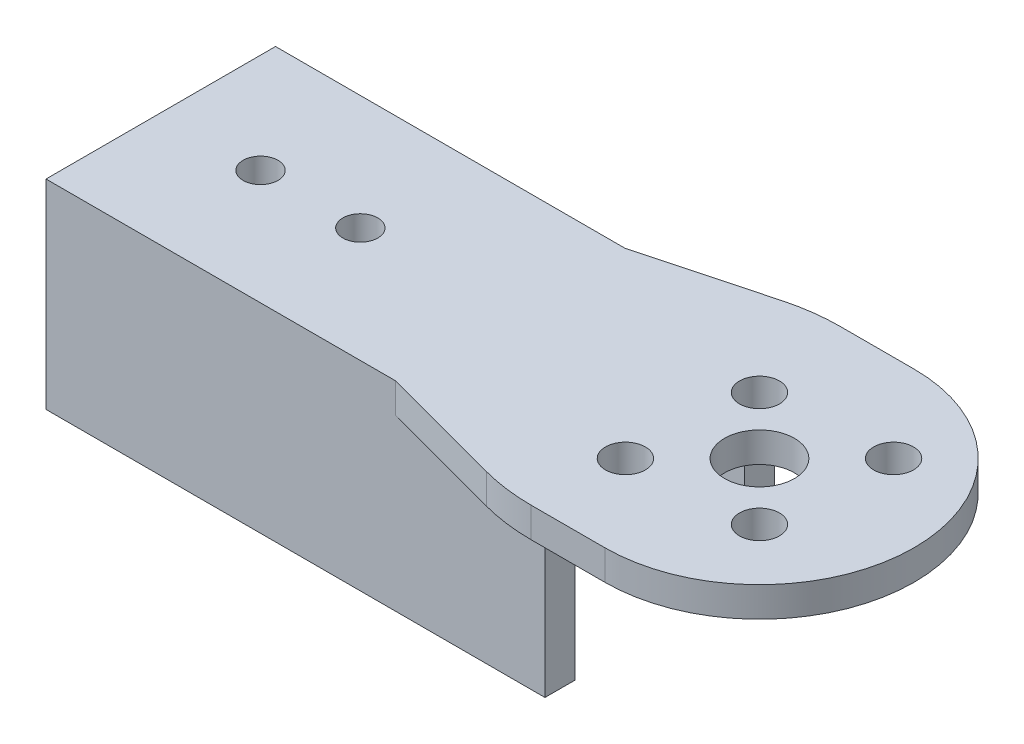
SolidWorks part; units mm, degrees
other "Markup1"
sketch "Sketch5" plane through (-25, 20, -29) normal (0, 1, 0) x (1, 0, 0)
sketch "Sketch6" plane through (-25, 20, -15) normal (0, 1, 0) x (1, 0, 0)
sketch "Sketch7" plane through (-25, 20, -15) normal (0, 1, 0) x (1, 0, 0)
sketch "Sketch8" plane through (-25, 20, -15.5) normal (0, 1, 0) x (1, 0, 0)
ref_plane "Front Plane" through (0, 0, 0) normal (0, 0, 1) x (1, 0, 0)
ref_plane "Top Plane" through (0, 0, 0) normal (0, 1, 0) x (1, 0, 0)
ref_plane "Right Plane" through (0, 0, 0) normal (1, 0, 0) x (0, 0, -1)
sketch "Sketch1" plane through (0, 0, 0) normal (0, 1, 0) x (1, 0, 0)
  line L1 (-25, 11.5) -> (25, 11.5)
  line L2 (-25, 11.5) -> (-25, -11.5)
  line L3 (-25, -11.5) -> (25, -11.5)
  line L4 (25, 11.5) -> (25, -11.5)
  line L5 (-25, 11.5) -> (25, -11.5) construction
  line L6 (-25, -11.5) -> (25, 11.5) construction
  point P0 (0, 0)
  dimension "D1" = 23
  dimension "D2" = 50
extrude "Boss-Extrude1" add sketch "Sketch1" along normal blind 20
sketch "Sketch2" plane through (25, 0, 0) normal (1, 0, 0) x (0, 0, -1)
  line L0 (55, 0) -> (-55, 0) construction
  line L1 (-8.5, 0) -> (8.5, 0)
  line L2 (-8.5, 0) -> (-8.5, 17)
  line L3 (-8.5, 17) -> (8.5, 17)
  line L4 (8.5, 0) -> (8.5, 17)
  line L5 (11.5, 20) -> (11.5, 0) construction
  line L6 (-11.5, 20) -> (-11.5, 0) construction
  line L7 (-11.5, 20) -> (11.5, 20) construction
  dimension "D1" = 3
  dimension "D2" = 3
  dimension "D3" = 3
extrude "Cut-Extrude1" cut sketch "Sketch2" against normal through all
sketch "Sketch3" plane through (0, 20, 0) normal (0, 1, 0) x (1, 0, 0)
  line L1 (25, 15.5) -> (35, 15.5)
  line L2 (25, 11.5) -> (25, -11.5)
  line L4 (25, -15.5) -> (35, -15.5)
  line L5 (25, 15.5) -> (10, 11.5)
  line L6 (25, 11.5) -> (-25, 11.5) construction
  line L7 (25, -15.5) -> (10, -11.5)
  line L8 (-25, -11.5) -> (25, -11.5) construction
  line L9 (10, -11.5) -> (25, -11.5)
  line L10 (10, 11.5) -> (25, 11.5)
  arc A0 (35, 15.5) -> (35, -15.5) centre (35, 0) cw
  dimension "D1" = 4
  dimension "D2" = 4
  dimension "D3" = 10
  dimension "D4" = 10
  dimension "D5" = 15
  dimension "D6" = 15
extrude "Boss-Extrude2" add sketch "Sketch3" against normal blind 3
sketch "Sketch4" plane through (0, 20, 0) normal (0, 1, 0) x (1, 0, 0)
  line L0 (35, 0) -> (50.5, 0) construction
  line L1 (-25, 11.5) -> (-25, -11.5) construction
  line L2 (41.7175, 6.7175) -> (35, 0) construction
  line L3 (35, 0) -> (28.2825, -6.7175) construction
  line L4 (35, 0) -> (40.7276, -5.7276) construction
  line L5 (29.2724, 5.7276) -> (35, 0) construction
  circle A0 centre (-15, 0) radius 1.75
  circle A1 centre (-5, 0) radius 1.75
  circle A2 centre (35, 0) radius 3.5
  circle A3 centre (28.2825, -6.7175) radius 2
  circle A4 centre (41.7175, 6.7175) radius 2
  arc A5 (35, -15.5) -> (35, 15.5) centre (35, 0) ccw construction
  circle A6 centre (40.7276, -5.7276) radius 2
  circle A7 centre (29.2724, 5.7276) radius 2
  point P21 (35, 0)
  point P26 (35, 0)
  dimension "D3" = 10
  dimension "D4" = 10
  dimension "D1" = 3.5
  dimension "D2" = 3.5
  dimension "D5" = 7
  dimension "D7" = 4
  dimension "D11" = 4
  dimension "D8" = 9.5
  dimension "D6" = 45
  dimension "D10" = 9.5
  dimension "D12" = 8.1
  dimension "D13" = 45
  dimension "D9" = 2
  dimension "D14" = 2
extrude "Cut-Extrude4" cut sketch "Sketch4" against normal through all
fillet "Fillet1" radius 20 2 edges at (25, 18.5, 15.5) (25, 18.5, -15.5)
equation "\"D2@Sketch3\"=\"D1@Sketch3\""
equation "\"D4@Sketch3\"=\"D3@Sketch3\""
equation "\"D6@Sketch3\"=\"D5@Sketch3\""
equation "\"D2@Sketch4\"=\"D1@Sketch4\""
equation "\"D10@Sketch4\"=\"D8@Sketch4\""
